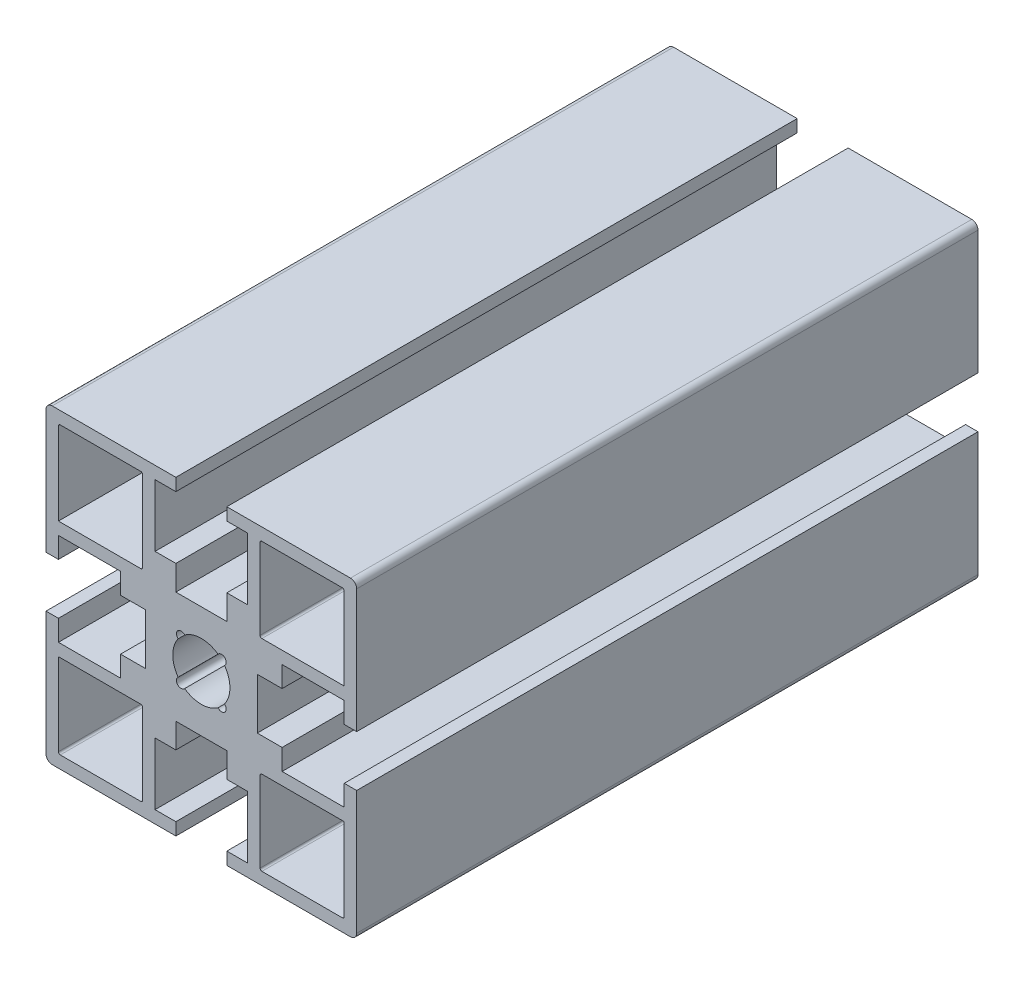
SolidWorks part; units mm, degrees
ref_plane "前视基准面" through (0, 0, 0) normal (0, 0, 1) x (1, 0, 0)
ref_plane "上视基准面" through (0, 0, 0) normal (0, 1, 0) x (1, 0, 0)
ref_plane "右视基准面" through (0, 0, 0) normal (1, 0, 0) x (0, 0, -1)
sketch "草图1" plane through (0, 0, 0) normal (0, 0, 1) x (1, 0, 0)
  line L0 (-4.3298, 24.1957) -> (-24.2298, 24.1957)
  line L1 (-25.2298, 23.1957) -> (-25.2298, 3.2957)
  line L2 (-4.3298, 22.1957) -> (-7.6798, 22.1957)
  line L3 (-23.2298, 8.6457) -> (-9.9798, 8.6457)
  line L4 (-9.6798, 8.9457) -> (-9.6798, 21.8957)
  line L5 (-9.9798, 22.1957) -> (-22.9298, 22.1957)
  line L6 (-23.2298, 21.8957) -> (-23.2298, 8.6457)
  line L7 (-23.2298, 6.6457) -> (-23.2298, 3.2957)
  line L8 (-9.2298, 3.2957) -> (-9.2298, -4.9043)
  line L9 (-4.3298, -9.8043) -> (3.8702, -9.8043)
  line L10 (8.7702, -4.9043) -> (8.7702, 3.2957)
  line L11 (3.8702, 8.1957) -> (-4.3298, 8.1957)
  line L14 (-4.3298, 12.1957) -> (-7.6798, 12.1957)
  line L15 (-13.2298, 6.6457) -> (-13.2298, 3.2957)
  line L16 (-23.2298, 6.6457) -> (-13.2298, 6.6457)
  line L17 (-25.2298, 3.2957) -> (-23.2298, 3.2957)
  line L18 (-7.6798, 22.1957) -> (-7.6798, 12.1957)
  line L19 (-4.3298, 24.1957) -> (-4.3298, 22.1957)
  line L20 (-13.2298, 3.2957) -> (-9.2298, 3.2957)
  line L21 (-4.3298, 12.1957) -> (-4.3298, 8.1957)
  line L22 (3.8702, 24.1957) -> (23.7702, 24.1957)
  line L23 (24.7702, 23.1957) -> (24.7702, 3.2957)
  line L24 (3.8702, 22.1957) -> (7.2202, 22.1957)
  line L25 (22.7702, 8.6457) -> (9.5202, 8.6457)
  line L26 (9.2202, 8.9457) -> (9.2202, 21.8957)
  line L27 (9.5202, 22.1957) -> (22.4702, 22.1957)
  line L28 (22.7702, 21.8957) -> (22.7702, 8.6457)
  line L29 (22.7702, 6.6457) -> (22.7702, 3.2957)
  line L32 (3.8702, 12.1957) -> (7.2202, 12.1957)
  line L33 (12.7702, 6.6457) -> (12.7702, 3.2957)
  line L34 (22.7702, 6.6457) -> (12.7702, 6.6457)
  line L35 (24.7702, 3.2957) -> (22.7702, 3.2957)
  line L36 (7.2202, 22.1957) -> (7.2202, 12.1957)
  line L37 (3.8702, 24.1957) -> (3.8702, 22.1957)
  line L38 (12.7702, 3.2957) -> (8.7702, 3.2957)
  line L39 (3.8702, 12.1957) -> (3.8702, 8.1957)
  line L40 (-4.3298, -25.8043) -> (-24.2298, -25.8043)
  line L41 (-25.2298, -24.8043) -> (-25.2298, -4.9043)
  line L42 (-4.3298, -23.8043) -> (-7.6798, -23.8043)
  line L43 (-23.2298, -10.2543) -> (-9.9798, -10.2543)
  line L44 (-9.6798, -10.5543) -> (-9.6798, -23.5043)
  line L45 (-9.9798, -23.8043) -> (-22.9298, -23.8043)
  line L46 (-23.2298, -23.5043) -> (-23.2298, -10.2543)
  line L47 (-23.2298, -8.2543) -> (-23.2298, -4.9043)
  line L50 (-4.3298, -13.8043) -> (-7.6798, -13.8043)
  line L51 (-13.2298, -8.2543) -> (-13.2298, -4.9043)
  line L52 (-23.2298, -8.2543) -> (-13.2298, -8.2543)
  line L53 (-25.2298, -4.9043) -> (-23.2298, -4.9043)
  line L54 (-7.6798, -23.8043) -> (-7.6798, -13.8043)
  line L55 (-4.3298, -25.8043) -> (-4.3298, -23.8043)
  line L56 (-13.2298, -4.9043) -> (-9.2298, -4.9043)
  line L57 (-4.3298, -13.8043) -> (-4.3298, -9.8043)
  line L58 (3.8702, -25.8043) -> (23.7702, -25.8043)
  line L59 (24.7702, -24.8043) -> (24.7702, -4.9043)
  line L60 (3.8702, -23.8043) -> (7.2202, -23.8043)
  line L61 (22.7702, -10.2543) -> (9.5202, -10.2543)
  line L62 (9.2202, -10.5543) -> (9.2202, -23.5043)
  line L63 (9.5202, -23.8043) -> (22.4702, -23.8043)
  line L64 (22.7702, -23.5043) -> (22.7702, -10.2543)
  line L65 (22.7702, -8.2543) -> (22.7702, -4.9043)
  line L68 (3.8702, -13.8043) -> (7.2202, -13.8043)
  line L69 (12.7702, -8.2543) -> (12.7702, -4.9043)
  line L70 (22.7702, -8.2543) -> (12.7702, -8.2543)
  line L71 (24.7702, -4.9043) -> (22.7702, -4.9043)
  line L72 (7.2202, -23.8043) -> (7.2202, -13.8043)
  line L73 (3.8702, -25.8043) -> (3.8702, -23.8043)
  line L74 (12.7702, -4.9043) -> (8.7702, -4.9043)
  line L75 (3.8702, -13.8043) -> (3.8702, -9.8043)
  arc A0 (-24.2298, 24.1957) -> (-25.2298, 23.1957) centre (-24.2298, 23.1957) ccw
  arc A1 (-9.9798, 8.6457) -> (-9.6798, 8.9457) centre (-9.9798, 8.9457) ccw
  arc A2 (-9.6798, 21.8957) -> (-9.9798, 22.1957) centre (-9.9798, 21.8957) ccw
  arc A3 (-22.9298, 22.1957) -> (-23.2298, 21.8957) centre (-22.9298, 21.8957) ccw
  arc A4 (2.4511, 2.9337) -> (-2.9107, 2.9337) centre (-0.2298, -0.8043) ccw
  arc A5 (-3.9678, 1.8766) -> (-3.9678, -3.4852) centre (-0.2298, -0.8043) ccw
  arc A6 (-2.9107, -4.5424) -> (2.4511, -4.5424) centre (-0.2298, -0.8043) ccw
  arc A7 (3.5082, -3.4852) -> (3.5082, 1.8766) centre (-0.2298, -0.8043) ccw
  arc A8 (3.5082, 1.8766) -> (2.4511, 2.9337) centre (3.0229, 2.4484) ccw
  arc A9 (-2.9107, 2.9337) -> (-3.9678, 1.8766) centre (-3.4825, 2.4484) ccw
  arc A10 (2.4511, -4.5424) -> (3.5082, -3.4852) centre (3.0229, -4.057) ccw
  arc A11 (-3.9678, -3.4852) -> (-2.9107, -4.5424) centre (-3.4825, -4.057) ccw
  arc A12 (24.7702, 23.1957) -> (23.7702, 24.1957) centre (23.7702, 23.1957) ccw
  arc A13 (9.2202, 8.9457) -> (9.5202, 8.6457) centre (9.5202, 8.9457) ccw
  arc A14 (9.5202, 22.1957) -> (9.2202, 21.8957) centre (9.5202, 21.8957) ccw
  arc A15 (22.7702, 21.8957) -> (22.4702, 22.1957) centre (22.4702, 21.8957) ccw
  arc A16 (-25.2298, -24.8043) -> (-24.2298, -25.8043) centre (-24.2298, -24.8043) ccw
  arc A17 (-9.6798, -10.5543) -> (-9.9798, -10.2543) centre (-9.9798, -10.5543) ccw
  arc A18 (-9.9798, -23.8043) -> (-9.6798, -23.5043) centre (-9.9798, -23.5043) ccw
  arc A19 (-23.2298, -23.5043) -> (-22.9298, -23.8043) centre (-22.9298, -23.5043) ccw
  arc A20 (23.7702, -25.8043) -> (24.7702, -24.8043) centre (23.7702, -24.8043) ccw
  arc A21 (9.5202, -10.2543) -> (9.2202, -10.5543) centre (9.5202, -10.5543) ccw
  arc A22 (9.2202, -23.5043) -> (9.5202, -23.8043) centre (9.5202, -23.5043) ccw
  arc A23 (22.4702, -23.8043) -> (22.7702, -23.5043) centre (22.4702, -23.5043) ccw
extrude "凸台-拉伸1" add sketch "草图1" along normal blind 100
